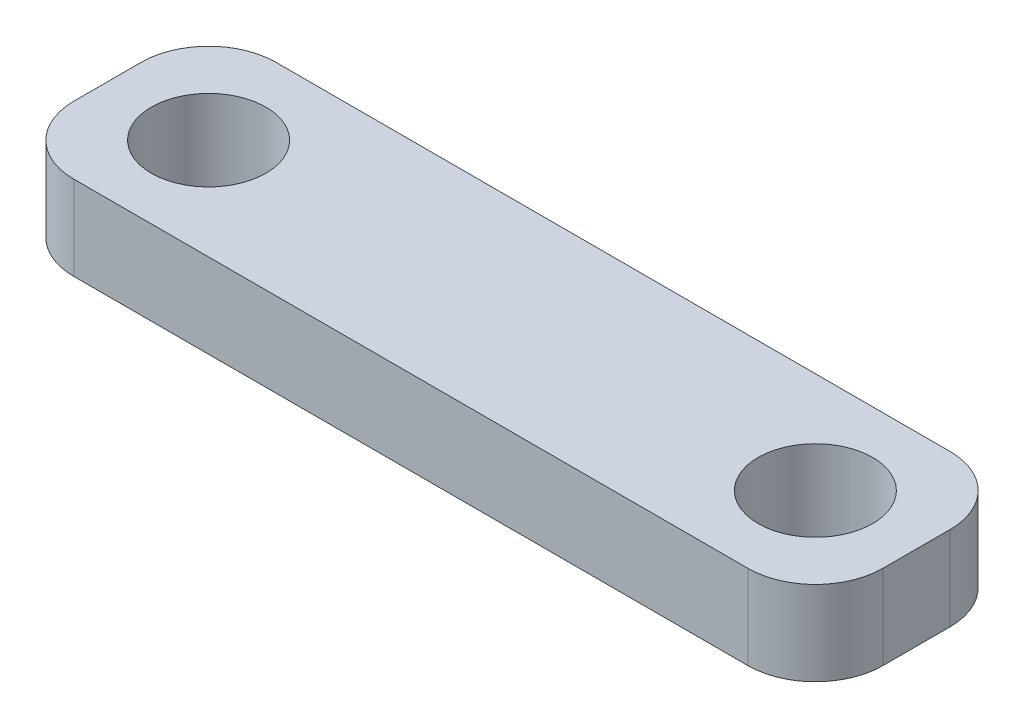
SolidWorks part; units mm, degrees
ref_plane "前视基准面" through (0, 0, 0) normal (0, 0, 1) x (1, 0, 0)
ref_plane "上视基准面" through (0, 0, 0) normal (0, 1, 0) x (1, 0, 0)
ref_plane "右视基准面" through (0, 0, 0) normal (1, 0, 0) x (0, 0, -1)
other "Configuration Table"
sketch "草图1" plane through (0, 0, 0) normal (0, 1, 0) x (1, 0, 0)
  line L0 (0, 0) -> (-9, 0) construction
  line L1 (-10, 3) -> (10, 3)
  line L2 (-12, 1) -> (-12, -1)
  line L3 (-10, -3) -> (10, -3)
  line L4 (12, 1) -> (12, -1)
  line L5 (-12, 3) -> (12, -3) construction
  line L6 (-12, -3) -> (12, 3) construction
  line L7 (-9, 0) -> (9, 0) construction
  arc A0 (10, -3) -> (12, -1) centre (10, -1) ccw
  arc A1 (10, 3) -> (12, 1) centre (10, 1) cw
  arc A2 (-12, -1) -> (-10, -3) centre (-10, -1) ccw
  arc A3 (-10, 3) -> (-12, 1) centre (-10, 1) ccw
  circle A4 centre (-9, 0) radius 1.7
  circle A5 centre (9, 0) radius 1.7
  point P0 (0, 0)
  dimension "D3" = 2
  dimension "D6" = 3.4
  dimension "D7" = 3.4
  dimension "D1" = 6
  dimension "D2" = 24
  dimension "D4" = 9
  dimension "D5" = 18
extrude "凸台-拉伸1" add sketch "草图1" along normal blind 2.5
